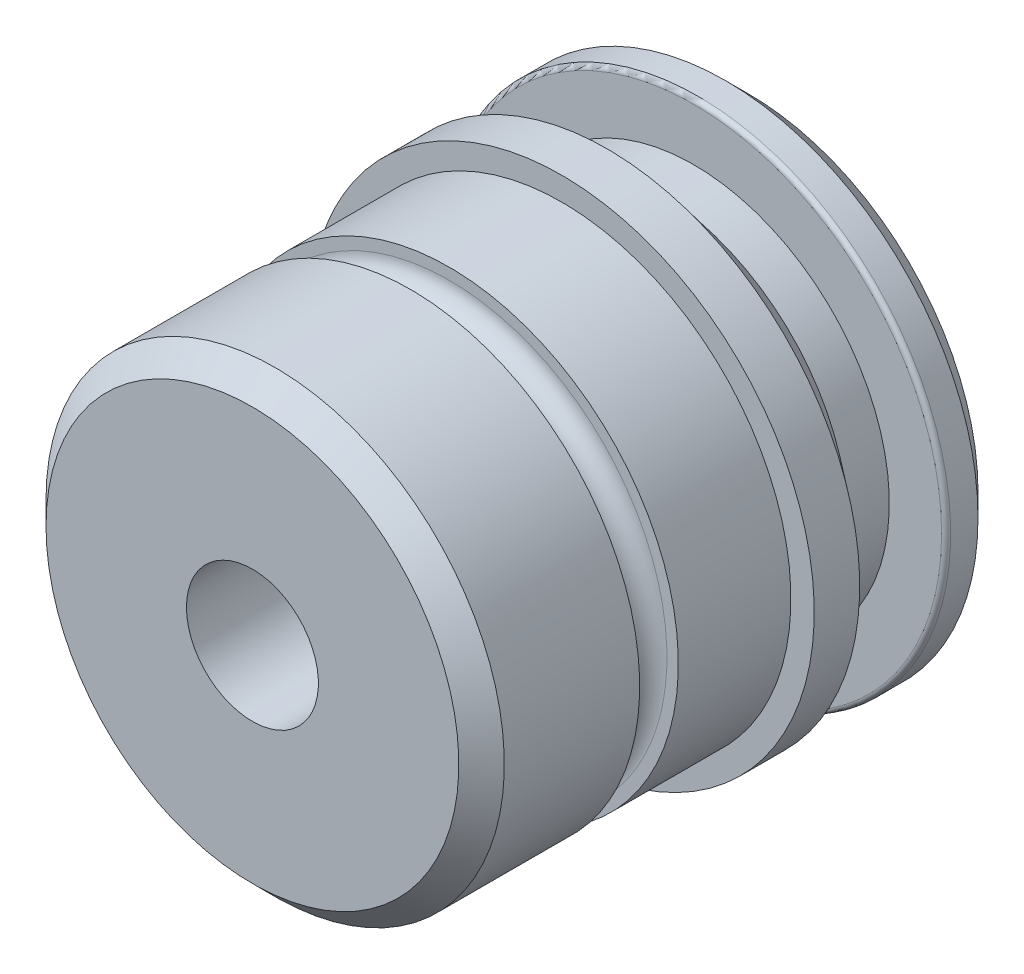
SolidWorks part; units mm, degrees
ref_plane "정면" through (0, 0, 0) normal (0, 0, 1) x (1, 0, 0)
ref_plane "윗면" through (0, 0, 0) normal (0, 1, 0) x (1, 0, 0)
ref_plane "우측면" through (0, 0, 0) normal (1, 0, 0) x (0, 0, -1)
sketch "스케치3" plane through (0, 0, 0) normal (0, 1, 0) x (1, 0, 0)
  line L0 (0, 0) -> (0, -21.8) construction
  line L1 (11.1, 0) -> (11.1, -2.4)
  line L2 (11.1, -2.4) -> (8.6, -2.4)
  line L3 (11.1, 0) -> (5.5, 0)
  line L4 (8.6, -2.4) -> (8.6, -4.2)
  line L5 (8.6, -4.2) -> (11.1, -6.2)
  line L6 (11.1, -6.2) -> (11.1, -8.2)
  line L7 (11.1, -8.2) -> (10.075, -8.2)
  line L8 (10.075, -8.2) -> (10.075, -13.15)
  line L9 (10.075, -13.15) -> (9.575, -13.15)
  line L10 (9.575, -14.85) -> (10.075, -14.85)
  line L11 (10.075, -14.85) -> (10.075, -21.8)
  line L12 (10.075, -21.8) -> (2.9, -21.8)
  line L13 (2.9, -21.8) -> (2.9, -11.8)
  line L14 (2.9, -11.8) -> (4.4, -11.8)
  line L15 (4.4, -11.8) -> (4.4, -10)
  line L16 (4.4, -10) -> (3.4, -10)
  line L17 (3.4, -10) -> (3.4, -8.2)
  line L18 (3.4, -8.2) -> (5.5, -7.6373)
  line L19 (5.5, -7.6373) -> (5.5, 0)
  line L20 (0, 0) -> (5.5, 0) construction
  arc A0 (9.575, -13.15) -> (9.575, -14.85) centre (9.575, -14) ccw
  dimension "D1" = 0.85
  dimension "D2" = 0.5
  dimension "D3" = 2.4
  dimension "D4" = 2
  dimension "D5" = 1.8
  dimension "D6" = 2
  dimension "D7" = 11
  dimension "D8" = 5.8
  dimension "D9" = 20.15
  dimension "D10" = 17.2
  dimension "D11" = 10
  dimension "D12" = 14
  dimension "D13" = 10
  dimension "D14" = 8.8
  dimension "D15" = 6.8
  dimension "D16" = 105
  dimension "D17" = 1.8
  dimension "D18" = 1.8
  dimension "D19" = 22.2
revolve "회전2" add sketch "스케치3" angle 360 about L0
chamfer "모따기1" distance 1 angle 45 2 edges at (-5.5, 0, 0) (-10.075, 0, 21.8)
chamfer "모따기2" distance 1 angle 45 1 edges at (-11.1, 0, 0)
fillet "필렛1" radius 0.2 1 edges at (-11.1, 0, 2.4)
